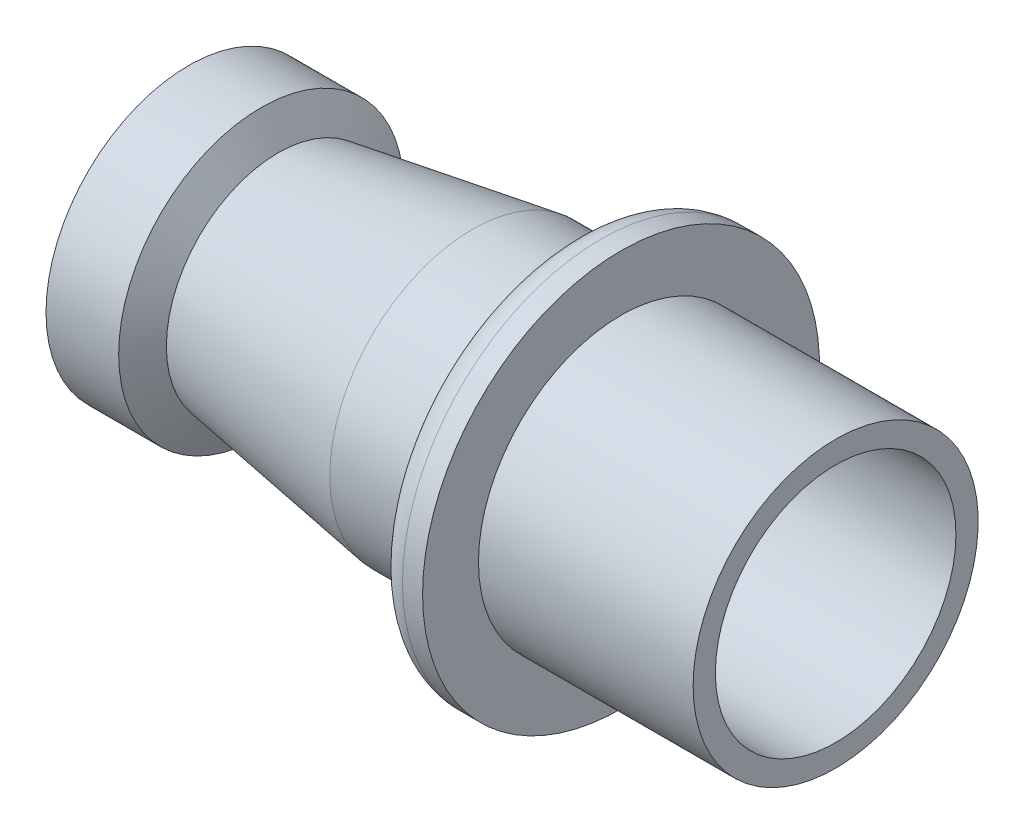
SolidWorks part; units mm, degrees
ref_plane "Front Plane" through (0, 0, 0) normal (0, 0, 1) x (1, 0, 0)
ref_plane "Top Plane" through (0, 0, 0) normal (0, 1, 0) x (1, 0, 0)
ref_plane "Right Plane" through (0, 0, 0) normal (1, 0, 0) x (0, 0, -1)
sketch "Sketch1" plane through (0, 0, 0) normal (0, 0, 1) x (1, 0, 0)
  line L0 (82.8943, 146.2953) -> (90.2545, 146.2953) construction
  line L1 (88.4765, 146.943) -> (88.8982, 146.943)
  line L2 (88.4765, 146.943) -> (88.4765, 147.7198) construction
  line L4 (87.1869, 146.943) -> (87.1869, 146.715)
  line L5 (89.302, 146.943) -> (89.302, 146.2953) construction
  line L6 (87.5171, 146.943) -> (87.5942, 146.8033)
  line L7 (87.1869, 146.943) -> (87.5171, 146.943)
  line L8 (88.4765, 146.943) -> (87.5942, 146.8033)
  line L9 (87.5942, 146.8033) -> (87.5942, 146.2953) construction
  line L10 (88.4765, 147.7198) -> (88.8982, 147.7198) construction
  line L11 (88.6289, 146.715) -> (87.1869, 146.715)
  line L12 (88.8982, 147.7198) -> (88.8982, 146.774) construction
  line L13 (88.9617, 147.197) -> (89.1522, 147.197)
  line L14 (90.1275, 146.943) -> (90.1275, 146.842)
  line L15 (90.1275, 146.842) -> (88.6289, 146.842)
  line L16 (88.6289, 146.842) -> (88.6289, 146.715)
  line L18 (89.1522, 146.943) -> (90.1275, 146.943)
  line L19 (89.1522, 147.197) -> (89.1522, 146.943)
  line L22 (88.8982, 146.943) -> (88.9617, 147.197)
  dimension "D1" = 188.997
revolve "Revolve1" add sketch "Sketch1" angle 360 about L0
fillet "Fillet1" radius 0.127
